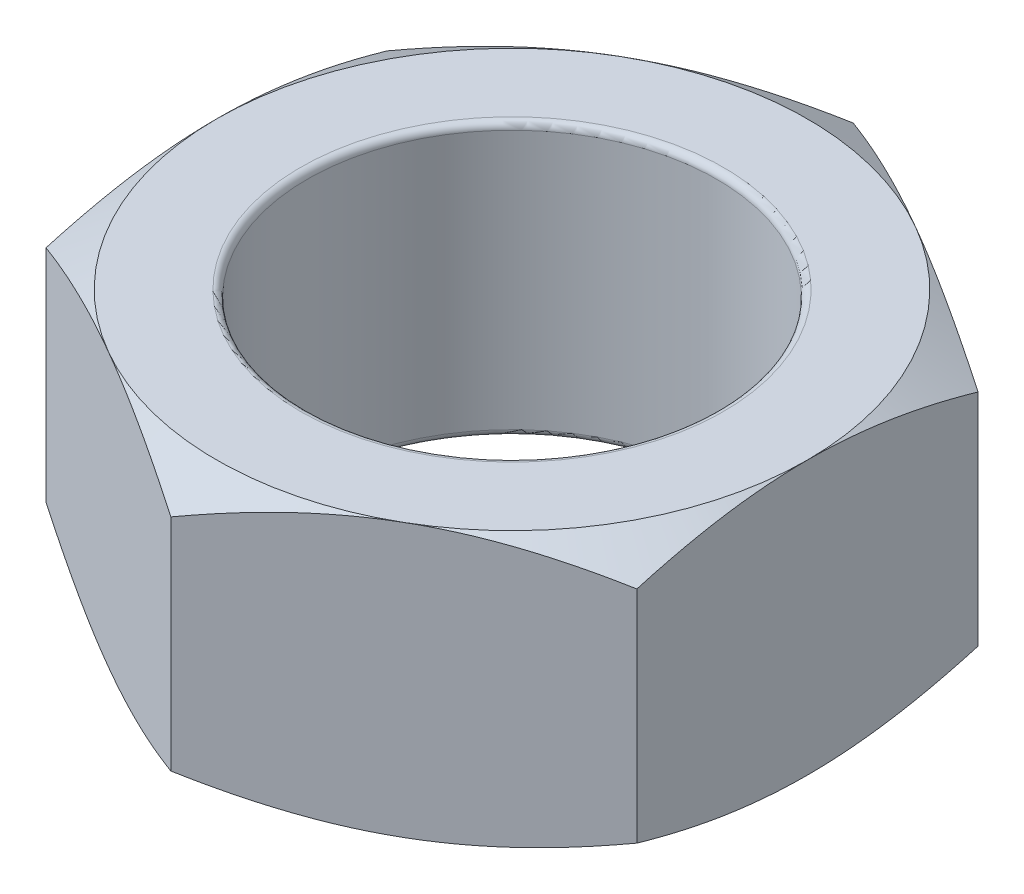
SolidWorks part; units mm, degrees
ref_plane "Front Plane" through (0, 0, 0) normal (0, 0, 1) x (1, 0, 0)
ref_plane "Top Plane" through (0, 0, 0) normal (0, 1, 0) x (1, 0, 0)
ref_plane "Right Plane" through (0, 0, 0) normal (1, 0, 0) x (0, 0, -1)
sketch "Sketch1" plane through (0, 0, 0) normal (0, 1, 0) x (1, 0, 0)
  line L1 (0, 2.5) -> (-2.1651, 1.25)
  line L2 (-2.1651, 1.25) -> (-2.1651, -1.25)
  line L3 (-2.1651, -1.25) -> (0, -2.5)
  line L4 (0, -2.5) -> (2.1651, -1.25)
  line L5 (2.1651, -1.25) -> (2.1651, 1.25)
  line L6 (2.1651, 1.25) -> (0, 2.5)
  circle A0 centre (0, 0) radius 1.5
  circle A1 centre (0, 0) radius 2.1651 construction
  dimension "D1" = 3
  dimension "D2" = 5
extrude "Boss-Extrude1" add sketch "Sketch1" along normal blind 2
sketch "Sketch2" plane through (0, 2, 0) normal (0, 1, 0) x (1, 0, 0)
  circle A0 centre (0, 0) radius 2.1651 construction
  circle A1 centre (0, 0) radius 2.1651
extrude "Cut-Extrude1" cut sketch "Sketch2" against normal blind 2 draft 60 flip side to cut
sketch "Sketch3" plane through (0, 0, 0) normal (0, -1, 0) x (1, 0, 0)
  circle A0 centre (0, 0) radius 2.1651 construction
  circle A1 centre (0, 0) radius 2.1651
extrude "Cut-Extrude2" cut sketch "Sketch3" against normal blind 2 draft 60 flip side to cut
fillet "Fillet1" radius 0.05 2 edges at (0, 0, 1.5) (0, 2, 1.5)
